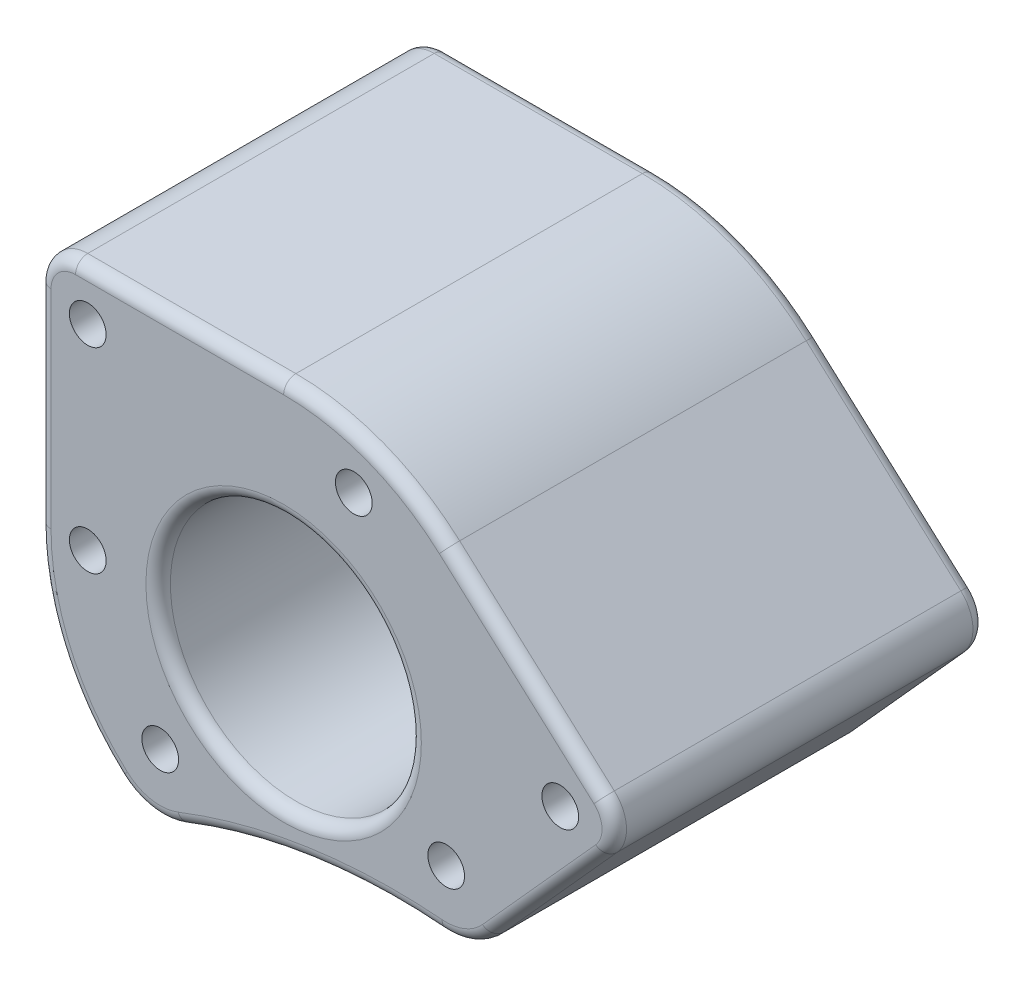
SolidWorks part; units mm, degrees
material "尼龙 101"
ref_plane "前视基准面" through (0, 0, 0) normal (0, 0, 1) x (1, 0, 0)
ref_plane "上视基准面" through (0, 0, 0) normal (0, 1, 0) x (1, 0, 0)
ref_plane "右视基准面" through (0, 0, 0) normal (1, 0, 0) x (0, 0, -1)
sketch "草图1" plane through (0, 0, 0) normal (0, 0, 1) x (1, 0, 0)
  line L0 (205.9514, 77) -> (205.9514, 60)
  line L1 (9.0486, 80) -> (225.9514, 80) construction
  line L2 (252.1895, 59.2508) -> (242.945, 48.9837)
  line L3 (239.334, 74.8629) -> (279.7648, 38.4589) construction
  line L4 (208.9514, 80) -> (225.9514, 80)
  line L5 (251.9675, 63.4877) -> (239.334, 74.8629)
  arc A0 (205.9514, 60) -> (212.512, 45.1885) centre (225.9514, 60) ccw
  arc A2 (217.6936, 44.235) -> (238.8264, 47.3456) centre (235, 0) cw
  circle A3 centre (235, 0) radius 47.25 construction
  arc A4 (212.512, 45.1885) -> (217.6936, 44.235) centre (215.8718, 48.8913) ccw
  arc A5 (238.8264, 47.3456) -> (242.945, 48.9837) centre (239.2292, 52.3294) ccw
  arc A6 (225.9514, 80) -> (239.334, 74.8629) centre (225.9514, 60) cw
  arc A7 (252.1895, 59.2508) -> (251.9675, 63.4877) centre (249.9601, 61.2582) ccw
  arc A8 (205.9514, 77) -> (208.9514, 80) centre (208.9514, 77) cw
  circle A9 centre (225.9514, 60) radius 10.25
  point P26 (254.1969, 61.4803)
  point P29 (205.9514, 80)
  dimension "D2" = 0.25
  dimension "D3" = 5
  dimension "D5" = 3
  dimension "D6" = 20.5
  dimension "D1" = 20
  dimension "D4" = 20
extrude "凸台-拉伸1" add sketch "草图1" along normal up to surface (30.3 mm away)
sketch "草图2" plane through (0, 0, 30.3) normal (0, 0, 1) x (1, 0, 0)
  line L0 (205.9514, 77) -> (205.9514, 60) construction
  line L1 (225.9514, 80) -> (208.9514, 80) construction
  line L2 (209.9514, 60) -> (205.9514, 60) construction
  line L3 (209.9514, 76) -> (209.9514, 60) construction
  line L4 (242.945, 48.9837) -> (252.1895, 59.2508) construction
  line L5 (251.9675, 63.4877) -> (239.334, 74.8629) construction
  line L6 (231.6853, 74.9373) -> (233.1188, 78.6716) construction
  circle A0 centre (215.8718, 48.8913) radius 1.5
  circle A1 centre (209.9514, 60) radius 1.5
  circle A2 centre (209.9514, 76) radius 1.5
  circle A3 centre (231.6853, 74.9373) radius 1.5
  circle A4 centre (239.2292, 52.3294) radius 1.5
  circle A5 centre (248.5478, 61.1842) radius 1.5
  arc A6 (212.512, 45.1885) -> (217.6936, 44.235) centre (215.8718, 48.8913) ccw construction
  arc A7 (238.8264, 47.3456) -> (242.945, 48.9837) centre (239.2292, 52.3294) ccw construction
  arc A9 (239.334, 74.8629) -> (225.9514, 80) centre (225.9514, 60) ccw construction
  point P26 (225.9514, 60)
  dimension "D1" = 3
  dimension "D2" = 4
  dimension "D3" = 4
  dimension "D4" = 4
  dimension "D5" = 4
  dimension "D6" = 4
extrude "切除-拉伸1" cut sketch "草图2" against normal through all both and the other way through all
fillet "圆角1" radius 1
